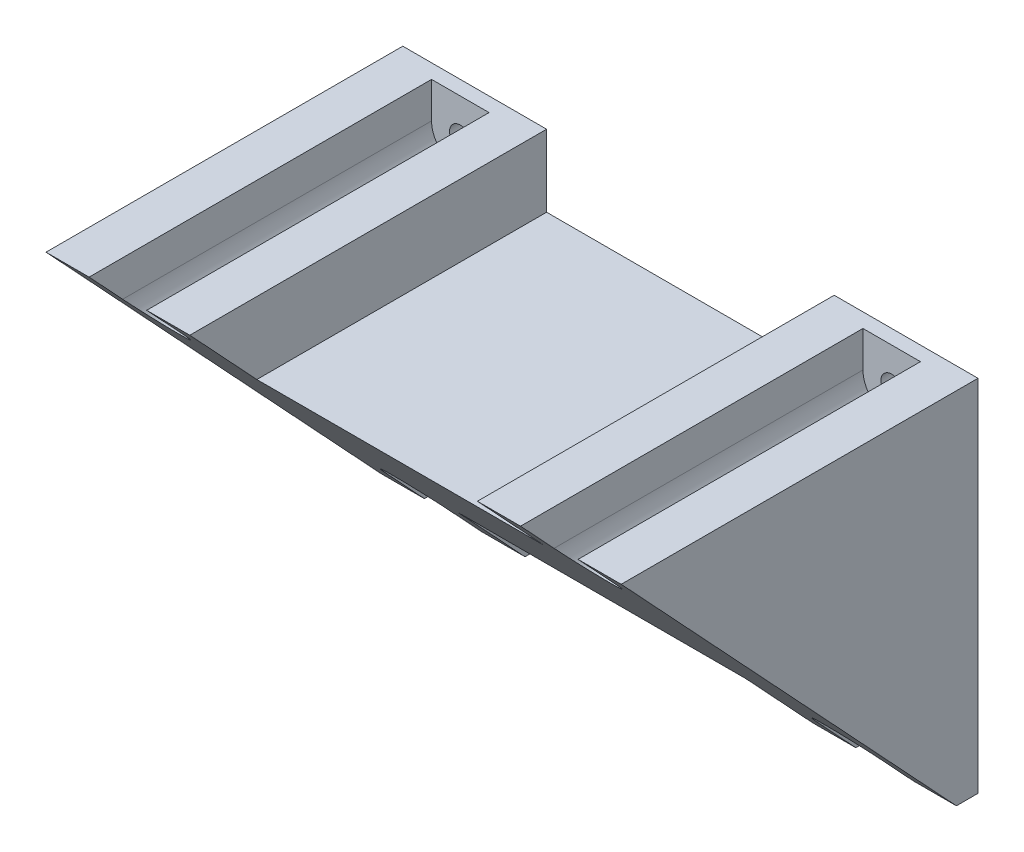
SolidWorks part; units mm, degrees
ref_plane "前视基准面" through (0, 0, 0) normal (0, 0, 1) x (1, 0, 0)
ref_plane "上视基准面" through (0, 0, 0) normal (0, 1, 0) x (1, 0, 0)
ref_plane "右视基准面" through (0, 0, 0) normal (1, 0, 0) x (0, 0, -1)
sketch "草图1" plane through (0, 0, 0) normal (0, 0, 1) x (1, 0, 0)
  line L0 (0, 0) -> (0, 50)
  line L1 (20, 50) -> (20, 40)
  line L2 (60, 40) -> (20, 40)
  line L3 (60, 50) -> (60, 40)
  line L4 (20, 50) -> (0, 50)
  line L5 (60, 50) -> (80, 50)
  line L6 (80, 50) -> (80, 0)
  line L7 (80, 0) -> (60, 0)
  line L8 (60, 0) -> (60, 10)
  line L9 (60, 10) -> (20, 10)
  line L10 (20, 10) -> (20, 0)
  line L11 (20, 0) -> (0, 0)
  point P13 (0, 0)
  point P14 (0, 0)
  dimension "D1" = 50
  dimension "D2" = 20
  dimension "D3" = 40
  dimension "D4" = 20
  dimension "D5" = 20
  dimension "D6" = 40
  dimension "D7" = 20
  dimension "D8" = 10
  dimension "D10" = 10
extrude "凸台-拉伸2" add sketch "草图1" along normal blind 2
sketch "草图3" plane through (0, 0, 2) normal (0, 0, 1) x (1, 0, 0)
  line L0 (10, 5) -> (10, 0) construction
  line L2 (20, 0) -> (0, 0) construction
  line L3 (10, 50) -> (10, 45) construction
  line L4 (20, 50) -> (0, 50) construction
  line L5 (70, 50) -> (70, 45) construction
  line L6 (60, 50) -> (80, 50) construction
  line L7 (70, 0) -> (70, 5) construction
  line L8 (80, 0) -> (60, 0) construction
  circle A1 centre (10, 45) radius 1.5
  circle A2 centre (10, 5) radius 1.5
  circle A3 centre (70, 45) radius 1.5
  circle A4 centre (70, 5) radius 1.5
  point P20 (0, 0)
  dimension "D1" = 3
  dimension "D4" = 3
  dimension "D5" = 3
  dimension "D6" = 3
  dimension "D2" = 40
  dimension "D3" = 40
  dimension "D7" = 60
  dimension "D8" = 60
  dimension "D9" = 10
  dimension "D10" = 10
  dimension "D11" = 10
  dimension "D12" = 10
extrude "切除-拉伸1" cut sketch "草图3" against normal through all
sketch "草图5" plane through (0, 0, 2) normal (0, 0, 1) x (1, 0, 0)
  line L0 (0, 50) -> (6, 50)
  line L1 (20, 50) -> (0, 50) construction
  line L2 (6, 50) -> (6, 45)
  line L3 (14, 45) -> (14, 50)
  line L4 (14, 50) -> (20, 50)
  line L5 (20, 50) -> (20, 40)
  line L6 (20, 40) -> (60, 40)
  line L7 (60, 40) -> (60, 50)
  line L8 (60, 50) -> (66, 50)
  line L9 (60, 50) -> (80, 50) construction
  line L10 (66, 50) -> (66, 45)
  line L11 (74, 45) -> (74, 50)
  line L12 (74, 50) -> (80, 50)
  line L13 (80, 50) -> (80, 0)
  line L14 (80, 0) -> (74, 0)
  line L15 (80, 0) -> (60, 0) construction
  line L16 (74, 0) -> (74, 5)
  line L17 (66, 5) -> (66, 0)
  line L18 (66, 0) -> (60, 0)
  line L19 (60, 0) -> (60, 10)
  line L20 (60, 10) -> (20, 10)
  line L21 (20, 10) -> (20, 0)
  line L22 (20, 0) -> (14, 0)
  line L23 (20, 0) -> (0, 0) construction
  line L24 (14, 0) -> (14, 5)
  line L25 (6, 5) -> (6, 0)
  line L26 (6, 0) -> (0, 0)
  line L27 (0, 0) -> (0, 50)
  arc A0 (6, 45) -> (14, 45) centre (10, 45) ccw
  arc A1 (66, 45) -> (74, 45) centre (70, 45) ccw
  arc A2 (74, 5) -> (66, 5) centre (70, 5) ccw
  arc A3 (14, 5) -> (6, 5) centre (10, 5) ccw
  dimension "D5" = 4
  dimension "D6" = 4
  dimension "D7" = 4
  dimension "D8" = 4
  dimension "D1" = 5
  dimension "D2" = 5
  dimension "D3" = 5
  dimension "D4" = 5
  dimension "D9" = 10
  dimension "D10" = 10
  dimension "D11" = 10
  dimension "D12" = 10
extrude "凸台-拉伸3" add sketch "草图5" along normal blind 1
draft "拔模4" type of draft neutral plane draft angle 43 faces to draft 1 face at (40, 25, 3) neutral plane through (20, 0, 2) neutral plane normal (0, -1, 0) parameters "D1"=43
